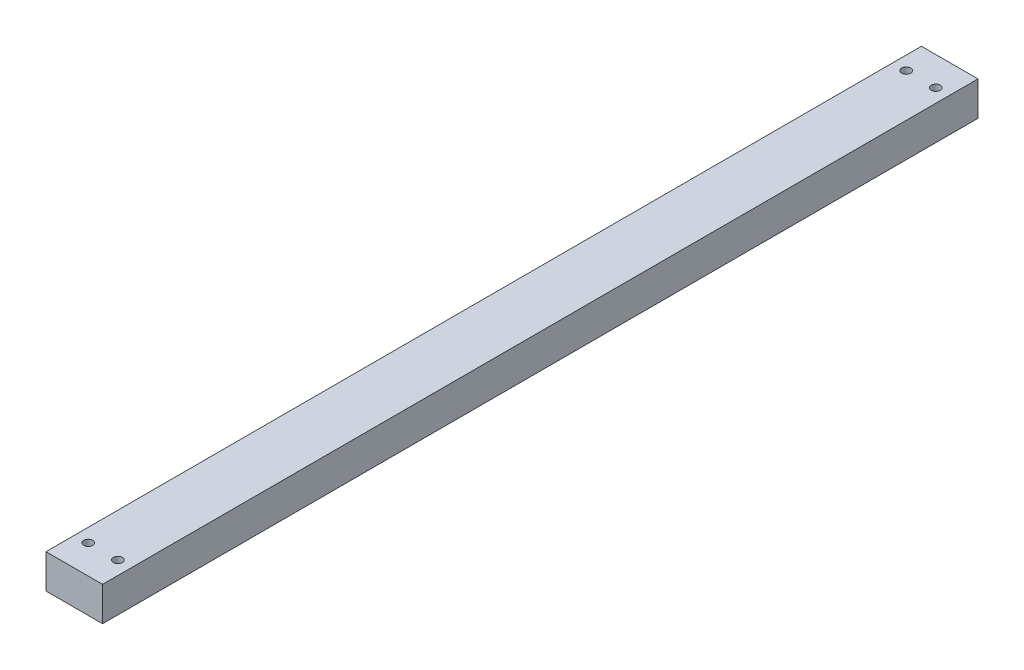
SolidWorks part; units mm, degrees
ref_plane "Front" through (0, 0, 0) normal (0, 0, 1) x (1, 0, 0)
ref_plane "Top" through (0, 0, 0) normal (0, 1, 0) x (1, 0, 0)
ref_plane "Right" through (0, 0, 0) normal (1, 0, 0) x (0, 0, -1)
sketch "Esquisse1" plane through (0, 0, 0) normal (0, 0, 1) x (1, 0, 0)
  line L1 (0, 0) -> (63, 0)
  line L2 (0, 0) -> (0, 38)
  line L3 (0, 38) -> (63, 38)
  line L4 (63, 0) -> (63, 38)
  dimension "D1" = 38
  dimension "D2" = 63
extrude "Boss.-Extru.1" add sketch "Esquisse1" along normal blind 975
sketch "Esquisse3" plane through (0, 38, 0) normal (0, 1, 0) x (1, 0, 0)
  line L0 (0, -32) -> (63, -32) construction
  line L3 (31.5, -32) -> (31.5, 0) construction
  line L5 (63, -487.5) -> (0, -487.5) construction
  line L6 (63, -975) -> (63, 0) construction
  line L7 (0, -975) -> (0, 0) construction
  line L8 (31.5, -943) -> (31.5, -975) construction
  line L9 (0, -943) -> (63, -943) construction
  line L10 (63, 0) -> (0, 0) construction
  line L11 (0, -975) -> (0, 0) construction
  circle A0 centre (15, -32) radius 5
  circle A1 centre (48, -32) radius 5
  circle A2 centre (48, -943) radius 5
  circle A3 centre (15, -943) radius 5
  point P2 (0, 0)
  point P5 (0, 0)
  point P8 (31.5, 0)
  point P9 (-10.458, -32)
  point P28 (0, 0)
  point P29 (0, -32)
  dimension "D1" = 10
  dimension "D2" = 32
  dimension "D3" = 33
extrude "Enlèv. mat.-Extru.1" cut sketch "Esquisse3" against normal through all
